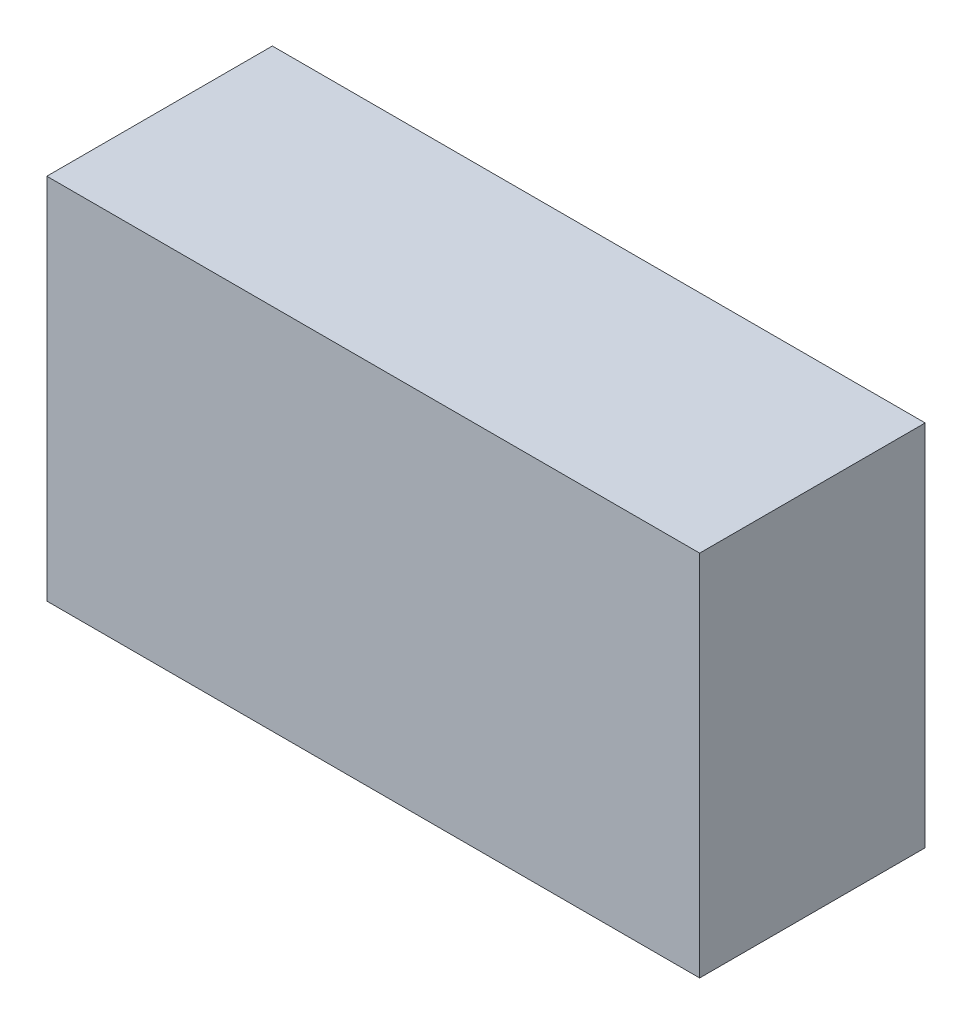
SolidWorks part; units mm, degrees
ref_plane "前视基准面" through (0, 0, 0) normal (0, 0, 1) x (1, 0, 0)
ref_plane "上视基准面" through (0, 0, 0) normal (0, 1, 0) x (1, 0, 0)
ref_plane "右视基准面" through (0, 0, 0) normal (1, 0, 0) x (0, 0, -1)
sketch "草图1" plane through (0, 0, 0) normal (0, 0, 1) x (1, 0, 0)
  line L1 (-42.0682, 49.8564) -> (12.9318, 49.8564)
  line L2 (-42.0682, 49.8564) -> (-42.0682, 18.8564)
  line L3 (-42.0682, 18.8564) -> (12.9318, 18.8564)
  line L4 (12.9318, 49.8564) -> (12.9318, 18.8564)
  dimension "D1" = 55
  dimension "D2" = 31
extrude "凸台-拉伸1" add sketch "草图1" along normal blind 19
